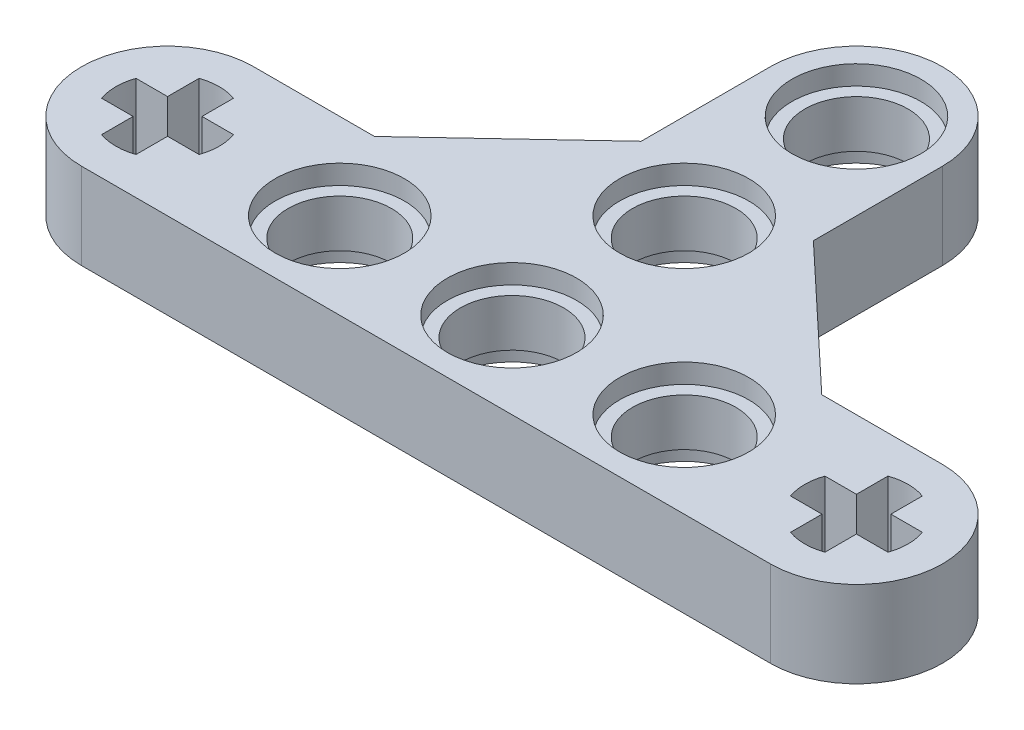
SolidWorks part; units mm, degrees
ref_plane "Front" through (0, 0, 0) normal (0, 0, 1) x (1, 0, 0)
ref_plane "Top" through (0, 0, 0) normal (0, 1, 0) x (1, 0, 0)
ref_plane "Right" through (0, 0, 0) normal (1, 0, 0) x (0, 0, -1)
sketch "草图1" plane through (0, 0, 0) normal (0, 1, 0) x (1, 0, 0)
  line L0 (0, 0) -> (0, 16) construction
  line L1 (0, 0) -> (16, 0) construction
  line L2 (-16, 0) -> (16, 0) construction
  line L3 (-16, 4) -> (-10.3889, 4)
  line L4 (-16, -4) -> (16, -4)
  line L5 (0, 0) -> (0, 16) construction
  line L6 (-4, 10) -> (-4, 16)
  line L7 (4, 10) -> (4, 16)
  line L8 (10.3889, 4) -> (16, 4)
  line L9 (-10.3889, 4) -> (-4, 10)
  line L10 (10.3889, 4) -> (4, 10)
  circle A0 centre (16, 0) radius 2.4
  circle A1 centre (8, 0) radius 2.4
  circle A2 centre (0, 0) radius 2.4
  circle A3 centre (-8, 0) radius 2.4
  circle A4 centre (-16, 0) radius 2.4
  circle A5 centre (0, 8) radius 2.4
  circle A6 centre (0, 16) radius 2.4
  arc A7 (-16, 4) -> (-16, -4) centre (-16, 0) ccw
  arc A8 (16, -4) -> (16, 4) centre (16, 0) ccw
  arc A10 (4, 16) -> (-4, 16) centre (0, 16) ccw
  point P5 (0, 0)
  point P22 (0, 8)
  dimension "D3" = 4.8
  dimension "D1" = 16
  dimension "D2" = 16
  dimension "D6" = 8
  dimension "D7" = 8
  dimension "D4" = 5
  dimension "D5" = 3
extrude "凸台-拉伸1" add sketch "草图1" along normal blind 4
sketch "草图2" plane through (0, 4, 0) normal (0, 1, 0) x (1, 0, 0)
  circle A0 centre (-16, 0) radius 3 construction
  circle A1 centre (-8, 0) radius 3
  circle A2 centre (0, 0) radius 3
  circle A3 centre (8, 0) radius 3
  circle A4 centre (16, 0) radius 3 construction
  circle A5 centre (0, 8) radius 3
  circle A6 centre (0, 16) radius 3
  dimension "D1" = 6
  dimension "D2" = 5
  dimension "D3" = 3
extrude "切除-拉伸1" cut sketch "草图2" against normal blind 0.9
ref_plane "基准面1" through (0, 2, 0) normal (0, 1, 0) x (1, 0, 0)
mirror "镜向1" about plane through (0, 2, 0) normal (0, 1, 0) of "切除-拉伸1"
sketch "草图4" plane through (0, 4, 0) normal (0, 1, 0) x (1, 0, 0)
  line L0 (-18.4, 0) -> (-13.6, 0) construction
  line L1 (-16, 2.4) -> (-16, -2.4) construction
  line L2 (-16.8, 2.4) -> (-16.8, -2.4)
  line L3 (-15.2, 2.4) -> (-15.2, -2.4)
  line L4 (-18.4, -0.8) -> (-13.6, -0.8)
  line L5 (-18.4, 0.8) -> (-13.6, 0.8)
  line L6 (0, -4) -> (0, 20) construction
  line L7 (-16, -4) -> (16, -4) construction
  line L8 (16, 2.4) -> (16, -2.4) construction
  line L9 (18.4, 0) -> (13.6, 0) construction
  line L10 (18.4, 0.8) -> (13.6, 0.8)
  line L11 (18.4, -0.8) -> (13.6, -0.8)
  line L12 (15.2, 2.4) -> (15.2, -2.4)
  line L13 (16.8, 2.4) -> (16.8, -2.4)
  circle A0 centre (-16, 0) radius 2.4 construction
  arc A1 (4, 16) -> (-4, 16) centre (0, 16) ccw construction
  circle A2 centre (16, 0) radius 2.4 construction
  circle A3 centre (16, 0) radius 2.4
  circle A4 centre (-16, 0) radius 2.4
  circle M19 centre (16, 0) radius 2.4
  circle M20 centre (-16, 0) radius 2.4
  dimension "D1" = 0.8
  dimension "D2" = 0.8
  dimension "D3" = 0.8
  dimension "D4" = 0.8
extrude "凸台-拉伸2" add sketch "草图4" against normal up to surface (4 mm away) contours L5 L2 M20 | L3 L5 M20 | L4 L3 M20 | L4 L2 M20 | L12 L10 M19 | L13 L10 M19 | L11 L13 M19 | L12 L11 M19 up to face at (-8, 0, 3)
